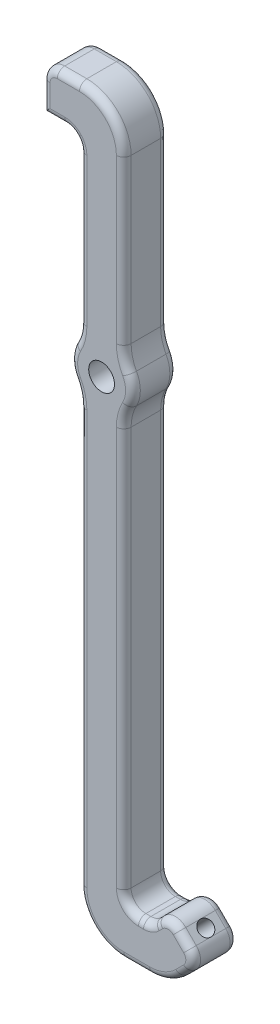
SolidWorks part; units mm, degrees
ref_plane "Plan de face" through (0, 0, 0) normal (0, 0, 1) x (1, 0, 0)
ref_plane "Plan de dessus" through (0, 0, 0) normal (0, 1, 0) x (1, 0, 0)
ref_plane "Plan de droite" through (0, 0, 0) normal (1, 0, 0) x (0, 0, -1)
sketch "Esquisse1" plane through (0, 0, 0) normal (0, 0, 1) x (1, 0, 0)
  line L1 (0, 0) -> (6, 0)
  line L2 (0, 0) -> (0, 100)
  line L3 (0, 100) -> (6, 100)
  line L4 (6, 0) -> (6, 100)
  dimension "D1" = 6
  dimension "D2" = 100
extrude "Boss.-Extru.1" add sketch "Esquisse1" along normal blind 6
sketch "Esquisse2" plane through (0, 0, 6) normal (0, 0, 1) x (1, 0, 0)
  line L2 (0, 100) -> (-5, 100)
  line L3 (0, 100) -> (0, 94)
  line L4 (0, 94) -> (-5, 94)
  line L5 (-5, 100) -> (-5, 94)
  dimension "D1" = 5
  dimension "D2" = 6
extrude "Boss.-Extru.2" add sketch "Esquisse2" against normal up to vertex (6 mm away) up to point (0, 100, 0)
sketch "Esquisse3" plane through (0, 0, 6) normal (0, 0, 1) x (1, 0, 0)
  line L0 (3, 0) -> (3, 67) construction
  line L1 (0, 0) -> (6, 0) construction
  line L3 (-5, 94) -> (0, 94) construction
  circle A0 centre (3, 67) radius 1.75
  circle A1 centre (3, 67) radius 4.25
  dimension "D1" = 3.5
  dimension "D2" = 2.5
  dimension "D3" = 27
extrude "Boss.-Extru.3" add sketch "Esquisse3" against normal blind 6
sketch "Esquisse4" plane through (0, 0, 6) normal (0, 0, 1) x (1, 0, 0)
  circle A0 centre (3, 67) radius 1.75
  dimension "D1" = 3.5
extrude "Enlèv. mat.-Extru.1" cut sketch "Esquisse4" against normal through all both and the other way through all
sketch "Esquisse5" plane through (0, 0, 6) normal (0, 0, 1) x (1, 0, 0)
  line L7 (6, 0) -> (12, 0)
  line L8 (12, 0) -> (16.2426, 4.2426)
  line L9 (16.2426, 4.2426) -> (12, 8.4853)
  line L10 (12, 8.4853) -> (9.5147, 6)
  line L11 (9.5147, 6) -> (6, 6)
  line L12 (6, 0) -> (6, 63.9896) construction
  line L13 (6, 6) -> (6, 0)
  dimension "D1" = 6
  dimension "D2" = 6
  dimension "D3" = 6
  dimension "D4" = 6
  dimension "D5" = 135
extrude "Boss.-Extru.4" add sketch "Esquisse5" against normal up to vertex (6 mm away) up to point (0, 0, 0)
fillet "Congé1" radius 6 7 edges at (0, 63.9896, 3) (0, 70.0104, 3) (6, 63.9896, 3) (6, 70.0104, 3) (6, 100, 3) (12, 0, 3) (0, 0, 3)
fillet "Congé2" radius 2 6 edges at (16.2426, 4.2426, 3) (12, 8.4853, 3) (9.5147, 6, 3) (6, 6, 3) (0, 94, 3) (-5, 100, 3)
sketch "Esquisse6" plane through (10.2426, 10.2426, 0) normal (0.7071, 0.7071, 0) x (0, 0, -1)
  line L0 (-6, -5.4853) -> (0, -5.4853) construction
  line L1 (-6, -6.4853) -> (-6, -4.4853) construction
  line L2 (0, -6.4853) -> (0, -4.4853) construction
  circle A0 centre (-3, -5.4853) radius 1
  dimension "D1" = 2
extrude "Enlèv. mat.-Extru.3" cut sketch "Esquisse6" against normal blind 6
fillet "Congé3" radius 1 54 edges at (-3.5, 94, 0) (-3.5, 94, 6) (-0.5858, 93.4142, 0) (0, 81.9527, 0) (-0.1858, 70.4238, 0) (-1.25, 67, 0) (-1.25, 67, 6) (-0.1858, 63.5762, 0) (-5, 96, 6) (-5, 96, 0) (-4.4142, 99.4142, 0) (-1.5, 100, 0) (4.2426, 98.2426, 0) (6, 82.9527, 0) (6.1858, 70.4238, 0) (7.25, 67, 6) (7.25, 67, 0) (6.1858, 63.5762, 0) (6, 35.0473, 0) (6.5858, 6.5858, 0) (8.3431, 6, 6) (8.3431, 6, 0) (9.4517, 6.1522, 0) (10.3431, 6.8284, 6) (10.3431, 6.8284, 0) (12, 7.6569, 0) (14.1213, 6.364, 6) (14.1213, 6.364, 0) (15.4142, 4.2426, 0) (14.2929, 2.2929, 0) (14.2929, 2.2929, 6) (11.8108, 0.4567, 0) (7.7574, 0, 0) (1.7574, 1.7574, 0) (-0.5858, 93.4142, 6) (0, 81.9527, 6) (-0.1858, 70.4238, 6) (-0.1858, 63.5762, 6) (-4.4142, 99.4142, 6) (-1.5, 100, 6) (4.2426, 98.2426, 6) (6, 82.9527, 6) (6.1858, 70.4238, 6) (6.1858, 63.5762, 6) (6, 35.0473, 6) (6.5858, 6.5858, 6) (9.4517, 6.1522, 6) (12, 7.6569, 6) (15.4142, 4.2426, 6) (11.8108, 0.4567, 6) (7.7574, 0, 6) (1.7574, 1.7574, 6) (0, 34.0473, 0) (0, 34.0473, 6)
